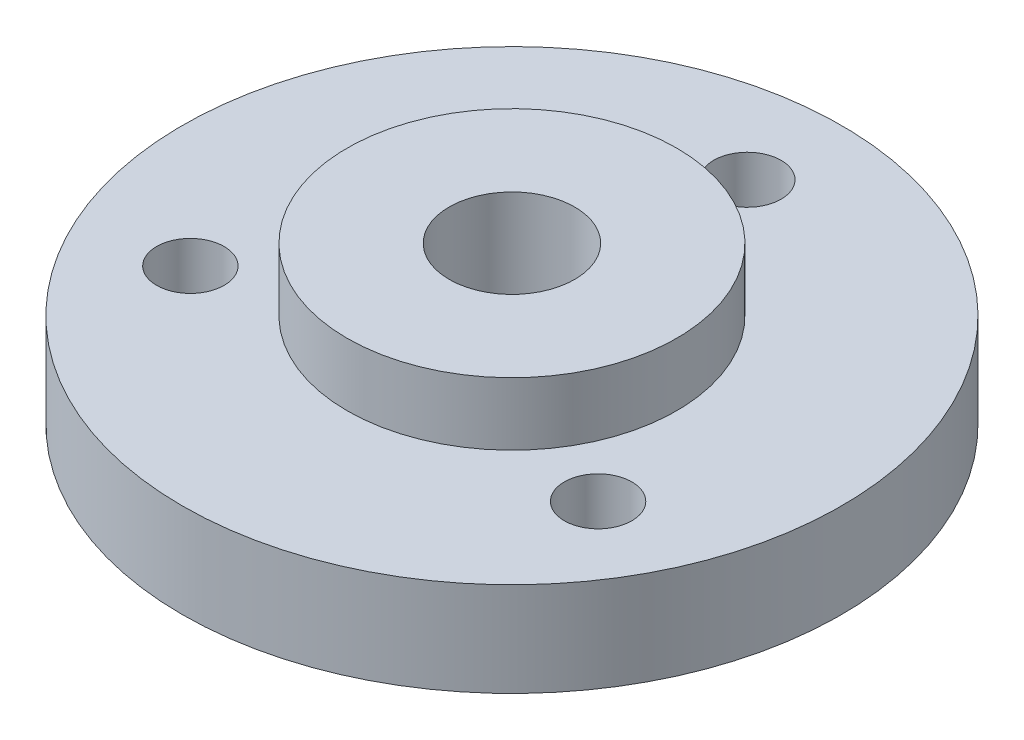
SolidWorks part; units mm, degrees
ref_plane "Front Plane" through (0, 0, 0) normal (0, 0, 1) x (1, 0, 0)
ref_plane "Top Plane" through (0, 0, 0) normal (0, 1, 0) x (1, 0, 0)
ref_plane "Right Plane" through (0, 0, 0) normal (1, 0, 0) x (0, 0, -1)
sketch "Sketch1" plane through (0, 0, 0) normal (0, 1, 0) x (1, 0, 0)
  line L0 (0, -44.7868) -> (0, 44.7868) construction
  circle A0 centre (0, 0) radius 4
  circle A2 centre (0, 0) radius 21
  circle A3 centre (0, 15) radius 2.15
  circle A4 centre (12.9904, -7.5) radius 2.15
  circle A5 centre (-12.9904, -7.5) radius 2.15
  circle A6 centre (0, 15) radius 4 construction
  circle A7 centre (12.9904, -7.5) radius 4 construction
  circle A8 centre (-12.9904, -7.5) radius 4 construction
  point P16 (0, 0)
  dimension "D1" = 8
  dimension "D2" = 42
  dimension "D3" = 4.3
  dimension "D6" = 8
  dimension "D4" = 15
  dimension "D5" = 3
extrude "Boss-Extrude1" add sketch "Sketch1" along normal blind 6
sketch "Sketch2" plane through (0, 6, 0) normal (0, 1, 0) x (1, 0, 0)
  circle A0 centre (0, 0) radius 10.5
  circle A1 centre (0, 0) radius 4
  dimension "D1" = 21
extrude "Boss-Extrude2" add sketch "Sketch2" along normal blind 4
